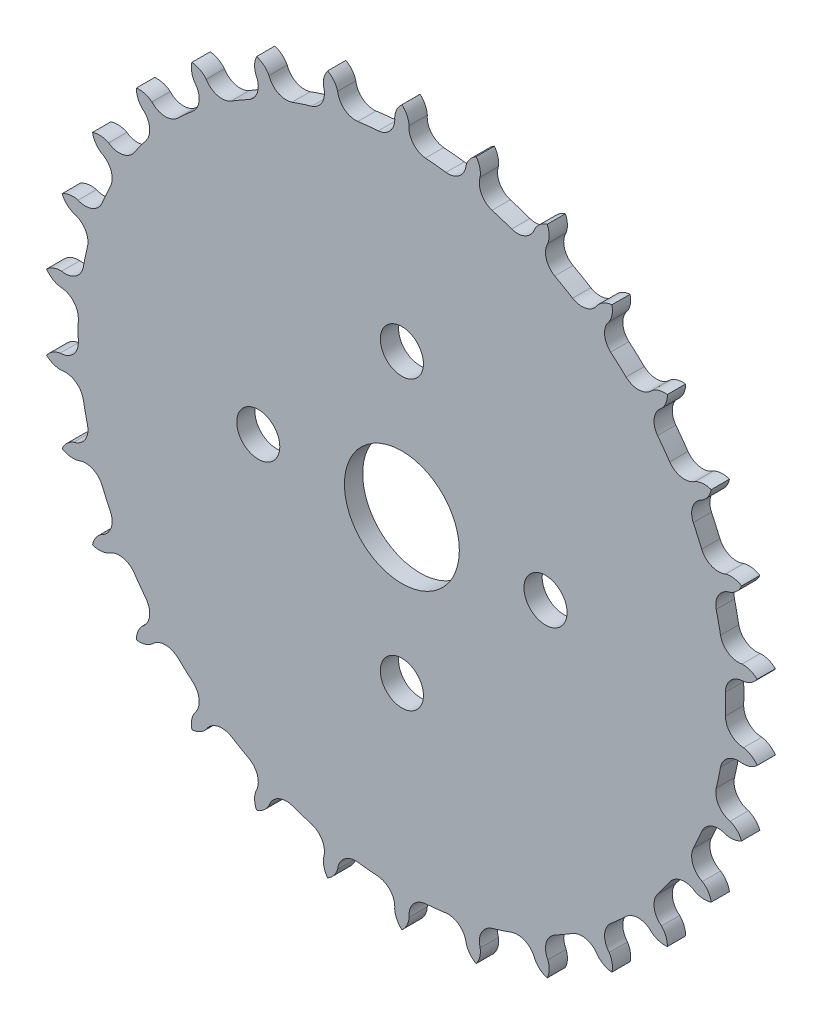
SolidWorks part; units mm, degrees
ref_plane "Front Plane" through (0, 0, 0) normal (0, 0, 1) x (1, 0, 0)
ref_plane "Top Plane" through (0, 0, 0) normal (0, 1, 0) x (1, 0, 0)
ref_plane "Right Plane" through (0, 0, 0) normal (1, 0, 0) x (0, 0, -1)
sketch "Sketch1" plane through (0, 0, 0) normal (0, 0, 1) x (1, 0, 0)
  circle A0 centre (0, 10) radius 1.5
  arc A1 (-10.6406, 19.8693) -> (-11.887, 19.1497) centre (0, 0) ccw
  arc A2 (0, 24.8732) -> (-0.5, 23.868) centre (0.9512, 23.7732) ccw
  arc A3 (0, 24.8732) -> (0.5, 23.868) centre (-0.9512, 23.7732) cw
  arc A4 (-0.5, 23.868) -> (-1.6391, 22.4794) centre (-1.7638, 23.7433) cw
  arc A5 (0.5, 23.868) -> (1.6391, 22.4794) centre (1.7638, 23.7433) ccw
  circle A6 centre (0, 0) radius 4
  circle A7 centre (10, 0) radius 1.5
  circle A8 centre (0, -10) radius 1.5
  circle A9 centre (-10, 0) radius 1.5
  arc A10 (5.1714, 24.3297) -> (4.4734, 23.4503) centre (5.8732, 23.0559) ccw
  arc A11 (5.1714, 24.3297) -> (5.4515, 23.2424) centre (4.0123, 23.4514) cw
  arc A12 (4.4734, 23.4503) -> (3.0704, 22.329) centre (3.2112, 23.5911) cw
  arc A13 (5.4515, 23.2424) -> (6.277, 21.6474) centre (6.6618, 22.8577) ccw
  arc A14 (10.1168, 22.7228) -> (9.2512, 22.0078) centre (10.5384, 21.331) ccw
  arc A15 (10.1168, 22.7228) -> (10.1647, 21.6011) centre (8.8004, 22.1048) cw
  arc A16 (9.2512, 22.0078) -> (7.6458, 21.2026) centre (8.0459, 22.408) cw
  arc A17 (10.1647, 21.6011) -> (10.6406, 19.8693) centre (11.2686, 20.9731) ccw
  arc A18 (14.6201, 20.1228) -> (13.6248, 19.6035) centre (14.7431, 18.6738) ccw
  arc A19 (14.6201, 20.1228) -> (14.4337, 19.0157) centre (13.204, 19.792) cw
  arc A20 (13.6248, 19.6035) -> (11.887, 19.1497) centre (12.529, 20.2455) cw
  arc A21 (14.4337, 19.0157) -> (14.5391, 17.2228) centre (15.3829, 18.1719) ccw
  arc A22 (18.4844, 16.6434) -> (17.4028, 16.3423) centre (18.3034, 15.2004) ccw
  arc A23 (18.4844, 16.6434) -> (18.0719, 15.5992) centre (17.0304, 16.6142) cw
  arc A24 (17.4028, 16.3423) -> (15.6087, 16.2598) centre (16.4645, 17.1981) cw
  arc A25 (18.0719, 15.5992) -> (17.8022, 13.8235) centre (18.8249, 14.5766) ccw
  arc A26 (21.5408, 12.4366) -> (20.4203, 12.367) centre (21.0638, 11.0628) ccw
  arc A27 (21.5408, 12.4366) -> (20.9202, 11.501) centre (20.1125, 12.7104) cw
  arc A28 (20.4203, 12.367) -> (18.6482, 12.6592) centre (19.6804, 13.3991) cw
  arc A29 (20.9202, 11.501) -> (20.2873, 9.8202) centre (21.4442, 10.3441) ccw
  arc A30 (23.6558, 7.6862) -> (22.5453, 7.8511) centre (22.9036, 6.4416) ccw
  arc A31 (23.6558, 7.6862) -> (22.8543, 6.9001) centre (22.3157, 8.251) cw
  arc A32 (22.5453, 7.8511) -> (20.8727, 8.5054) centre (22.0361, 9.0146) cw
  arc A33 (22.8543, 6.9001) -> (21.8857, 5.3876) centre (23.1262, 5.6596) ccw
  arc A34 (24.7369, 2.6) -> (23.685, 2.9921) centre (23.7424, 1.539) ccw
  arc A35 (24.7369, 2.6) -> (23.7895, 1.9977) centre (23.5435, 3.431) cw
  arc A36 (23.685, 2.9921) -> (22.1849, 3.9799) centre (23.4288, 4.236) cw
  arc A37 (23.7895, 1.9977) -> (22.5276, 0.7196) centre (23.7976, 0.7277) ccw
  arc A38 (24.7369, -2.6) -> (23.7895, -1.9977) centre (23.5435, -3.431) ccw
  arc A39 (24.7369, -2.6) -> (23.685, -2.9921) centre (23.7424, -1.539) cw
  arc A40 (23.7895, -1.9977) -> (22.5276, -0.7196) centre (23.7976, -0.7277) cw
  arc A41 (23.685, -2.9921) -> (22.1849, -3.9799) centre (23.4288, -4.236) ccw
  arc A42 (23.6558, -7.6862) -> (22.8543, -6.9001) centre (22.3157, -8.251) ccw
  arc A43 (23.6558, -7.6862) -> (22.5453, -7.8511) centre (22.9036, -6.4416) cw
  arc A44 (22.8543, -6.9001) -> (21.8857, -5.3876) centre (23.1262, -5.6596) cw
  arc A45 (22.5453, -7.8511) -> (20.8727, -8.5054) centre (22.0361, -9.0146) ccw
  arc A46 (21.5408, -12.4366) -> (20.9202, -11.501) centre (20.1125, -12.7104) ccw
  arc A47 (21.5408, -12.4366) -> (20.4203, -12.367) centre (21.0638, -11.0628) cw
  arc A48 (20.9202, -11.501) -> (20.2873, -9.8202) centre (21.4442, -10.3441) cw
  arc A49 (20.4203, -12.367) -> (18.6482, -12.6592) centre (19.6804, -13.3991) ccw
  arc A50 (18.4844, -16.6434) -> (18.0719, -15.5992) centre (17.0304, -16.6142) ccw
  arc A51 (18.4844, -16.6434) -> (17.4028, -16.3423) centre (18.3034, -15.2004) cw
  arc A52 (18.0719, -15.5992) -> (17.8022, -13.8235) centre (18.8249, -14.5766) cw
  arc A53 (17.4028, -16.3423) -> (15.6087, -16.2598) centre (16.4645, -17.1981) ccw
  arc A54 (14.6201, -20.1228) -> (14.4337, -19.0157) centre (13.204, -19.792) ccw
  arc A55 (14.6201, -20.1228) -> (13.6248, -19.6035) centre (14.7431, -18.6738) cw
  arc A56 (14.4337, -19.0157) -> (14.5391, -17.2228) centre (15.3829, -18.1719) cw
  arc A57 (13.6248, -19.6035) -> (11.887, -19.1497) centre (12.529, -20.2455) ccw
  arc A58 (10.1168, -22.7228) -> (10.1647, -21.6011) centre (8.8004, -22.1048) ccw
  arc A59 (10.1168, -22.7228) -> (9.2512, -22.0078) centre (10.5384, -21.331) cw
  arc A60 (10.1647, -21.6011) -> (10.6406, -19.8693) centre (11.2686, -20.9731) cw
  arc A61 (9.2512, -22.0078) -> (7.6458, -21.2026) centre (8.0459, -22.408) ccw
  arc A62 (5.1714, -24.3297) -> (5.4515, -23.2424) centre (4.0123, -23.4514) ccw
  arc A63 (5.1714, -24.3297) -> (4.4734, -23.4503) centre (5.8732, -23.0559) cw
  arc A64 (5.4515, -23.2424) -> (6.277, -21.6474) centre (6.6618, -22.8577) cw
  arc A65 (4.4734, -23.4503) -> (3.0704, -22.329) centre (3.2112, -23.5911) ccw
  arc A66 (0, -24.8732) -> (0.5, -23.868) centre (-0.9512, -23.7732) ccw
  arc A67 (0, -24.8732) -> (-0.5, -23.868) centre (0.9512, -23.7732) cw
  arc A68 (0.5, -23.868) -> (1.6391, -22.4794) centre (1.7638, -23.7433) cw
  arc A69 (-0.5, -23.868) -> (-1.6391, -22.4794) centre (-1.7638, -23.7433) ccw
  arc A70 (-5.1714, -24.3297) -> (-4.4734, -23.4503) centre (-5.8732, -23.0559) ccw
  arc A71 (-5.1714, -24.3297) -> (-5.4515, -23.2424) centre (-4.0123, -23.4514) cw
  arc A72 (-4.4734, -23.4503) -> (-3.0704, -22.329) centre (-3.2112, -23.5911) cw
  arc A73 (-5.4515, -23.2424) -> (-6.277, -21.6474) centre (-6.6618, -22.8577) ccw
  arc A74 (-10.1168, -22.7228) -> (-9.2512, -22.0078) centre (-10.5384, -21.331) ccw
  arc A75 (-10.1168, -22.7228) -> (-10.1647, -21.6011) centre (-8.8004, -22.1048) cw
  arc A76 (-9.2512, -22.0078) -> (-7.6458, -21.2026) centre (-8.0459, -22.408) cw
  arc A77 (-10.1647, -21.6011) -> (-10.6406, -19.8693) centre (-11.2686, -20.9731) ccw
  arc A78 (-14.6201, -20.1228) -> (-13.6248, -19.6035) centre (-14.7431, -18.6738) ccw
  arc A79 (-14.6201, -20.1228) -> (-14.4337, -19.0157) centre (-13.204, -19.792) cw
  arc A80 (-13.6248, -19.6035) -> (-11.887, -19.1497) centre (-12.529, -20.2455) cw
  arc A81 (-14.4337, -19.0157) -> (-14.5391, -17.2228) centre (-15.3829, -18.1719) ccw
  arc A82 (-18.4844, -16.6434) -> (-17.4028, -16.3423) centre (-18.3034, -15.2004) ccw
  arc A83 (-18.4844, -16.6434) -> (-18.0719, -15.5992) centre (-17.0304, -16.6142) cw
  arc A84 (-17.4028, -16.3423) -> (-15.6087, -16.2598) centre (-16.4645, -17.1981) cw
  arc A85 (-18.0719, -15.5992) -> (-17.8022, -13.8235) centre (-18.8249, -14.5766) ccw
  arc A86 (-21.5408, -12.4366) -> (-20.4203, -12.367) centre (-21.0638, -11.0628) ccw
  arc A87 (-21.5408, -12.4366) -> (-20.9202, -11.501) centre (-20.1125, -12.7104) cw
  arc A88 (-20.4203, -12.367) -> (-18.6482, -12.6592) centre (-19.6804, -13.3991) cw
  arc A89 (-20.9202, -11.501) -> (-20.2873, -9.8202) centre (-21.4442, -10.3441) ccw
  arc A90 (-23.6558, -7.6862) -> (-22.5453, -7.8511) centre (-22.9036, -6.4416) ccw
  arc A91 (-23.6558, -7.6862) -> (-22.8543, -6.9001) centre (-22.3157, -8.251) cw
  arc A92 (-22.5453, -7.8511) -> (-20.8727, -8.5054) centre (-22.0361, -9.0146) cw
  arc A93 (-22.8543, -6.9001) -> (-21.8857, -5.3876) centre (-23.1262, -5.6596) ccw
  arc A94 (-24.7369, -2.6) -> (-23.685, -2.9921) centre (-23.7424, -1.539) ccw
  arc A95 (-24.7369, -2.6) -> (-23.7895, -1.9977) centre (-23.5435, -3.431) cw
  arc A96 (-23.685, -2.9921) -> (-22.1849, -3.9799) centre (-23.4288, -4.236) cw
  arc A97 (-23.7895, -1.9977) -> (-22.5276, -0.7196) centre (-23.7976, -0.7277) ccw
  arc A98 (-24.7369, 2.6) -> (-23.7895, 1.9977) centre (-23.5435, 3.431) ccw
  arc A99 (-24.7369, 2.6) -> (-23.685, 2.9921) centre (-23.7424, 1.539) cw
  arc A100 (-23.7895, 1.9977) -> (-22.5276, 0.7196) centre (-23.7976, 0.7277) cw
  arc A101 (-23.685, 2.9921) -> (-22.1849, 3.9799) centre (-23.4288, 4.236) ccw
  arc A102 (-23.6558, 7.6862) -> (-22.8543, 6.9001) centre (-22.3157, 8.251) ccw
  arc A103 (-23.6558, 7.6862) -> (-22.5453, 7.8511) centre (-22.9036, 6.4416) cw
  arc A104 (-22.8543, 6.9001) -> (-21.8857, 5.3876) centre (-23.1262, 5.6596) cw
  arc A105 (-22.5453, 7.8511) -> (-20.8727, 8.5054) centre (-22.0361, 9.0146) ccw
  arc A106 (-21.5408, 12.4366) -> (-20.9202, 11.501) centre (-20.1125, 12.7104) ccw
  arc A107 (-21.5408, 12.4366) -> (-20.4203, 12.367) centre (-21.0638, 11.0628) cw
  arc A108 (-20.9202, 11.501) -> (-20.2873, 9.8202) centre (-21.4442, 10.3441) cw
  arc A109 (-20.4203, 12.367) -> (-18.6482, 12.6592) centre (-19.6804, 13.3991) ccw
  arc A110 (-18.4844, 16.6434) -> (-18.0719, 15.5992) centre (-17.0304, 16.6142) ccw
  arc A111 (-18.4844, 16.6434) -> (-17.4028, 16.3423) centre (-18.3034, 15.2004) cw
  arc A112 (-18.0719, 15.5992) -> (-17.8022, 13.8235) centre (-18.8249, 14.5766) cw
  arc A113 (-17.4028, 16.3423) -> (-15.6087, 16.2598) centre (-16.4645, 17.1981) ccw
  arc A114 (-14.6201, 20.1228) -> (-14.4337, 19.0157) centre (-13.204, 19.792) ccw
  arc A115 (-14.6201, 20.1228) -> (-13.6248, 19.6035) centre (-14.7431, 18.6738) cw
  arc A116 (-14.4337, 19.0157) -> (-14.5391, 17.2228) centre (-15.3829, 18.1719) cw
  arc A117 (-13.6248, 19.6035) -> (-11.887, 19.1497) centre (-12.529, 20.2455) ccw
  arc A118 (-10.1168, 22.7228) -> (-10.1647, 21.6011) centre (-8.8004, 22.1048) ccw
  arc A119 (-10.1168, 22.7228) -> (-9.2512, 22.0078) centre (-10.5384, 21.331) cw
  arc A120 (-10.1647, 21.6011) -> (-10.6406, 19.8693) centre (-11.2686, 20.9731) cw
  arc A121 (-9.2512, 22.0078) -> (-7.6458, 21.2026) centre (-8.0459, 22.408) ccw
  arc A122 (-5.1714, 24.3297) -> (-5.4515, 23.2424) centre (-4.0123, 23.4514) ccw
  arc A123 (-5.1714, 24.3297) -> (-4.4734, 23.4503) centre (-5.8732, 23.0559) cw
  arc A124 (-5.4515, 23.2424) -> (-6.277, 21.6474) centre (-6.6618, 22.8577) cw
  arc A125 (-4.4734, 23.4503) -> (-3.0704, 22.329) centre (-3.2112, 23.5911) ccw
  arc A126 (-6.277, 21.6474) -> (-7.6458, 21.2026) centre (0, 0) ccw
  arc A127 (-1.6391, 22.4794) -> (-3.0704, 22.329) centre (0, 0) ccw
  arc A128 (3.0704, 22.329) -> (1.6391, 22.4794) centre (0, 0) ccw
  arc A129 (7.6458, 21.2026) -> (6.277, 21.6474) centre (0, 0) ccw
  arc A130 (11.887, 19.1497) -> (10.6406, 19.8693) centre (0, 0) ccw
  arc A131 (15.6087, 16.2598) -> (14.5391, 17.2228) centre (0, 0) ccw
  arc A132 (18.6482, 12.6592) -> (17.8022, 13.8235) centre (0, 0) ccw
  arc A133 (20.8727, 8.5054) -> (20.2873, 9.8202) centre (0, 0) ccw
  arc A134 (22.1849, 3.9799) -> (21.8857, 5.3876) centre (0, 0) ccw
  arc A135 (22.5276, -0.7196) -> (22.5276, 0.7196) centre (0, 0) ccw
  arc A136 (21.8857, -5.3876) -> (22.1849, -3.9799) centre (0, 0) ccw
  arc A137 (-14.5391, 17.2228) -> (-15.6087, 16.2598) centre (0, 0) ccw
  arc A138 (-17.8022, 13.8235) -> (-18.6482, 12.6592) centre (0, 0) ccw
  arc A139 (-20.2873, 9.8202) -> (-20.8727, 8.5054) centre (0, 0) ccw
  arc A140 (-21.8857, 5.3876) -> (-22.1849, 3.9799) centre (0, 0) ccw
  arc A141 (-22.5276, 0.7196) -> (-22.5276, -0.7196) centre (0, 0) ccw
  arc A142 (-22.1849, -3.9799) -> (-21.8857, -5.3876) centre (0, 0) ccw
  arc A143 (-20.8727, -8.5054) -> (-20.2873, -9.8202) centre (0, 0) ccw
  arc A144 (-18.6482, -12.6592) -> (-17.8022, -13.8235) centre (0, 0) ccw
  arc A145 (-15.6087, -16.2598) -> (-14.5391, -17.2228) centre (0, 0) ccw
  arc A146 (-11.887, -19.1497) -> (-10.6406, -19.8693) centre (0, 0) ccw
  arc A147 (-7.6458, -21.2026) -> (-6.277, -21.6474) centre (0, 0) ccw
  arc A148 (-3.0704, -22.329) -> (-1.6391, -22.4794) centre (0, 0) ccw
  arc A149 (1.6391, -22.4794) -> (3.0704, -22.329) centre (0, 0) ccw
  arc A150 (6.277, -21.6474) -> (7.6458, -21.2026) centre (0, 0) ccw
  arc A151 (10.6406, -19.8693) -> (11.887, -19.1497) centre (0, 0) ccw
  arc A152 (14.5391, -17.2228) -> (15.6087, -16.2598) centre (0, 0) ccw
  arc A153 (17.8022, -13.8235) -> (18.6482, -12.6592) centre (0, 0) ccw
  arc A154 (20.2873, -9.8202) -> (20.8727, -8.5054) centre (0, 0) ccw
  dimension "D1" = 4
  dimension "D2" = 30
extrude "Boss-Extrude1" add sketch "Sketch1" along normal blind 1.27
